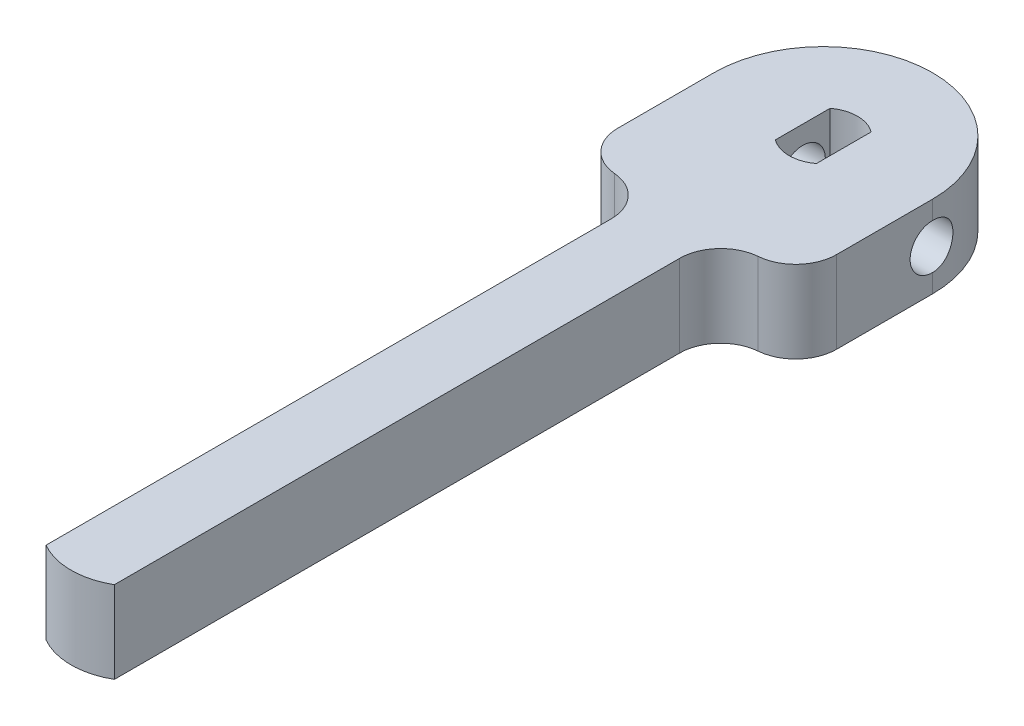
SolidWorks part; units mm, degrees
ref_plane "Plan de face" through (0, 0, 0) normal (0, 0, 1) x (1, 0, 0)
ref_plane "Plan de dessus" through (0, 0, 0) normal (0, 1, 0) x (1, 0, 0)
ref_plane "Plan de droite" through (0, 0, 0) normal (1, 0, 0) x (0, 0, -1)
sketch "Esquisse1" plane through (0, 0, 0) normal (0, 1, 0) x (1, 0, 0)
  line L0 (0, 0) -> (0, -50) construction
  line L1 (8, 0) -> (8, -10)
  line L2 (-8, 0) -> (-8, -10)
  line L3 (1.5, 2) -> (1.5, -2)
  line L4 (-1.5, 2) -> (-1.5, -2)
  line L5 (-8, -10) -> (-2.5, -10)
  line L6 (-2.5, -10) -> (-2.5, -54.3301)
  line L7 (8, -10) -> (2.5, -10)
  line L8 (2.5, -10) -> (2.5, -54.3301)
  arc A0 (8, 0) -> (-8, 0) centre (0, 0) ccw
  arc A1 (-2.5, -54.3301) -> (2.5, -54.3301) centre (0, -50) ccw
  arc A2 (-1.5, -2) -> (1.5, -2) centre (0, 0) ccw
  arc A3 (1.5, 2) -> (-1.5, 2) centre (0, 0) ccw
  point P3 (11.7563, -10)
  dimension "D1" = 5
  dimension "D2" = 8
  dimension "D5" = 5
  dimension "D6" = 10
  dimension "D7" = 5
  dimension "D3" = 3
  dimension "D4" = 50
extrude "Boss.-Extru.1" add sketch "Esquisse1" along normal blind 6 contours L2 L5 L6 A1 L8 L7 L1 A0 | A2 L3 A3 L4
hole_wizard "Trou pour taraudage pour trou taraudé M41" positions "Esquisse2" profile "Esquisse3" hole size "M4" standard "ISO" end condition through all
sketch "Esquisse2" plane through (8, 0, 0) normal (1, 0, 0) x (0, 0, -1)
  line L0 (0, 6) -> (0, 0) construction
  point P0 (0, 3)
sketch "Esquisse3" plane through (8, 3, 0) normal (0, 1, 0) x (0, 0, -1)
  line L0 (0, 0) -> (0, 16)
  line L1 (0, 16) -> (1.65, 16)
  line L2 (1.65, 16) -> (1.65, 0)
  line L5 (1.65, 0) -> (0, 0)
  line L11 (0, -6.35) -> (0, 107.95) construction
  dimension "Diamètre du perçage jusqu'au prochain" = 3.3
  dimension "Profondeur du perçage jusqu'au prochain" = 16
fillet "Congé1" radius 3 1 edges at (-2.5, 3, 10)
fillet "Congé2" radius 3 2 edges at (-8, 3, 10) (2.5, 3, 10)
fillet "Congé3" radius 3 1 edges at (8, 3, 10)
